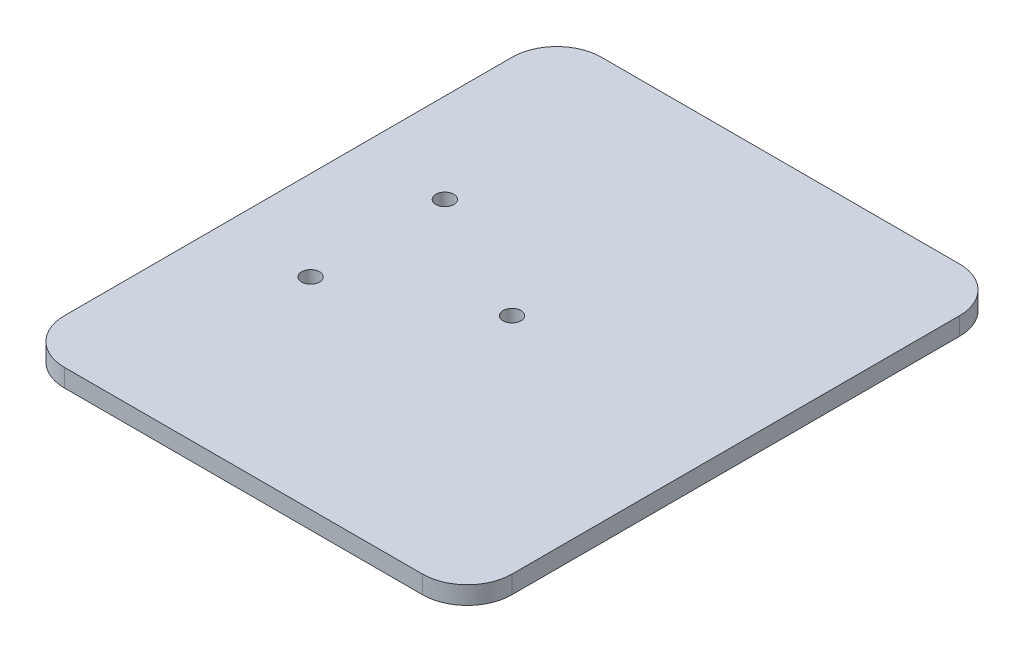
SolidWorks part; units mm, degrees
ref_plane "Front Plane" through (0, 0, 0) normal (0, 0, 1) x (1, 0, 0)
ref_plane "Top Plane" through (0, 0, 0) normal (0, 1, 0) x (1, 0, 0)
ref_plane "Right Plane" through (0, 0, 0) normal (1, 0, 0) x (0, 0, -1)
sketch "Sketch1" plane through (0, 0, 0) normal (0, 1, 0) x (1, 0, 0)
  line L1 (-52.2549, 26.2745) -> (-12.2549, 26.2745)
  line L2 (-57.2549, 21.2745) -> (-57.2549, -28.7255)
  line L3 (-52.2549, -33.7255) -> (-12.2549, -33.7255)
  line L4 (-7.2549, 21.2745) -> (-7.2549, -28.7255)
  arc A0 (-57.2549, -28.7255) -> (-52.2549, -33.7255) centre (-52.2549, -28.7255) ccw
  arc A1 (-12.2549, -33.7255) -> (-7.2549, -28.7255) centre (-12.2549, -28.7255) ccw
  arc A2 (-12.2549, 26.2745) -> (-7.2549, 21.2745) centre (-12.2549, 21.2745) cw
  arc A3 (-52.2549, 26.2745) -> (-57.2549, 21.2745) centre (-52.2549, 21.2745) ccw
  circle A4 centre (-32.2549, -3.7255) radius 1
  circle A5 centre (-47.2549, 3.7745) radius 1
  circle A6 centre (-47.2549, -11.2255) radius 1
  point P6 (-57.2549, -33.7255)
  point P11 (-7.2549, 26.2745)
  point P14 (-57.2549, 26.2745)
  dimension "D3" = 5
  dimension "D4" = 30
  dimension "D6" = 22.5
  dimension "D8" = 15
  dimension "D1" = 60
  dimension "D2" = 50
  dimension "D5" = 25
  dimension "D7" = 10
  dimension "D9" = 10
extrude "Boss-Extrude1" add sketch "Sketch1" along normal blind 2
